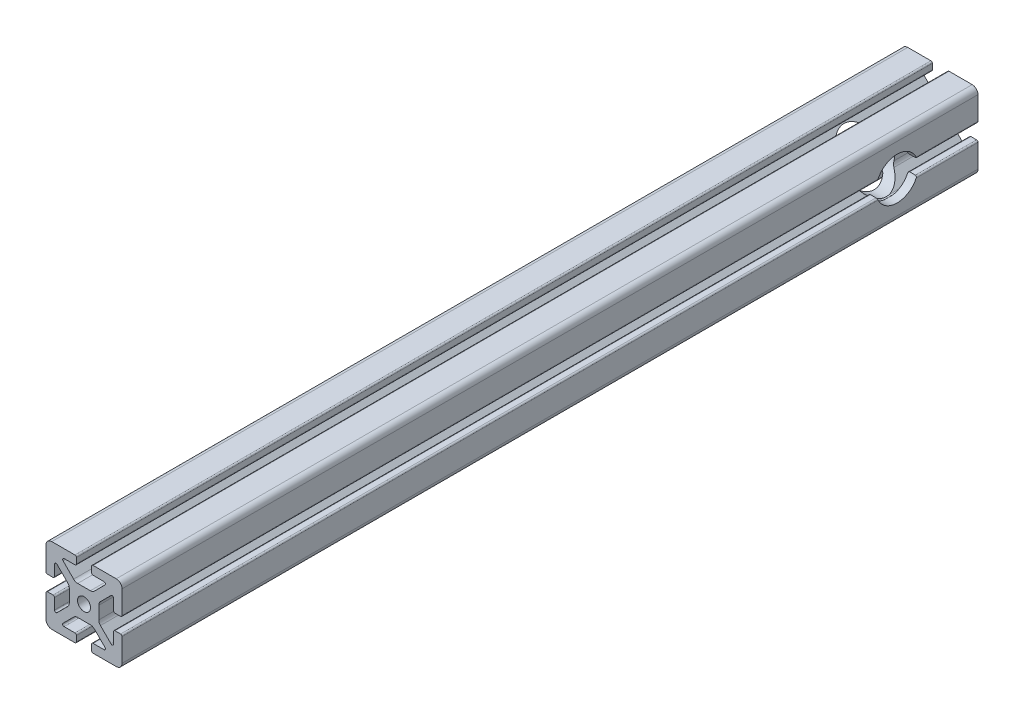
SolidWorks part; units mm, degrees
ref_plane "Front Plane" through (0, 0, 0) normal (0, 0, 1) x (1, 0, 0)
ref_plane "Top Plane" through (0, 0, 0) normal (0, 1, 0) x (1, 0, 0)
ref_plane "Right Plane" through (0, 0, 0) normal (1, 0, 0) x (0, 0, -1)
sketch "Sketch1" plane through (0, 0, 0) normal (0, 0, 1) x (1, 0, 0)
  line L0 (0, 20) -> (0, -20) construction
  line L1 (-20, 0) -> (20, 0) construction
  line L2 (-20, 16.952) -> (-20, 4.7625)
  line L3 (-16.952, 20) -> (-4.7625, 20)
  line L4 (-4.0005, 19.238) -> (-4.0005, 16.2662)
  line L5 (-4.7625, 15.5042) -> (-10.4856, 15.5042)
  line L6 (-11.0244, 14.2034) -> (-5.456, 8.6351)
  line L7 (-14.2034, 11.0244) -> (-8.6351, 5.456)
  line L8 (-15.5042, 10.4856) -> (-15.5042, 4.7625)
  line L9 (-16.2662, 4.0005) -> (-19.238, 4.0005)
  line L10 (0, 0) -> (-20, 20) construction
  line L11 (-3.3367, 7.7572) -> (3.3367, 7.7572)
  line L12 (-7.7572, 3.3367) -> (-7.7572, -3.3367)
  line L13 (16.2662, 4.0005) -> (19.238, 4.0005)
  line L14 (15.5042, 10.4856) -> (15.5042, 4.7625)
  line L15 (20, 16.952) -> (20, 4.7625)
  line L16 (16.952, 20) -> (4.7625, 20)
  line L17 (4.0005, 19.238) -> (4.0005, 16.2662)
  line L18 (4.7625, 15.5042) -> (10.4856, 15.5042)
  line L19 (7.7572, 3.3367) -> (7.7572, -3.3367)
  line L20 (11.0244, 14.2034) -> (5.456, 8.6351)
  line L21 (14.2034, 11.0244) -> (8.6351, 5.456)
  line L22 (-16.2662, -4.0005) -> (-19.238, -4.0005)
  line L23 (-15.5042, -10.4856) -> (-15.5042, -4.7625)
  line L24 (-14.2034, -11.0244) -> (-8.6351, -5.456)
  line L25 (-11.0244, -14.2034) -> (-5.456, -8.6351)
  line L26 (-4.7625, -15.5042) -> (-10.4856, -15.5042)
  line L27 (-4.0005, -19.238) -> (-4.0005, -16.2662)
  line L28 (-16.952, -20) -> (-4.7625, -20)
  line L29 (-20, -16.952) -> (-20, -4.7625)
  line L30 (20, -16.952) -> (20, -4.7625)
  line L31 (16.952, -20) -> (4.7625, -20)
  line L32 (4.0005, -19.238) -> (4.0005, -16.2662)
  line L33 (4.7625, -15.5042) -> (10.4856, -15.5042)
  line L34 (11.0244, -14.2034) -> (5.456, -8.6351)
  line L35 (14.2034, -11.0244) -> (8.6351, -5.456)
  line L36 (15.5042, -10.4856) -> (15.5042, -4.7625)
  line L37 (16.2662, -4.0005) -> (19.238, -4.0005)
  line L38 (-3.3367, -7.7572) -> (3.3367, -7.7572)
  circle A0 centre (0, 0) radius 3.4036
  arc A1 (-20, 16.952) -> (-16.952, 20) centre (-16.952, 16.952) cw
  arc A2 (-14.2034, 11.0244) -> (-15.5042, 10.4856) centre (-14.7422, 10.4856) ccw
  arc A3 (-10.4856, 15.5042) -> (-11.0244, 14.2034) centre (-10.4856, 14.7422) ccw
  arc A4 (-4.7625, 20) -> (-4.0005, 19.238) centre (-4.7625, 19.238) cw
  arc A5 (-20, 4.7625) -> (-19.238, 4.0005) centre (-19.238, 4.7625) ccw
  arc A6 (-15.5042, 4.7625) -> (-16.2662, 4.0005) centre (-16.2662, 4.7625) cw
  arc A7 (-4.0005, 16.2662) -> (-4.7625, 15.5042) centre (-4.7625, 16.2662) cw
  arc A8 (-3.3367, 7.7572) -> (-5.456, 8.6351) centre (-3.3367, 10.7544) cw
  arc A9 (-7.7572, 3.3367) -> (-8.6351, 5.456) centre (-10.7544, 3.3367) ccw
  arc A10 (15.5042, 4.7625) -> (16.2662, 4.0005) centre (16.2662, 4.7625) ccw
  arc A11 (20, 4.7625) -> (19.238, 4.0005) centre (19.238, 4.7625) cw
  arc A12 (20, 16.952) -> (16.952, 20) centre (16.952, 16.952) ccw
  arc A13 (4.7625, 20) -> (4.0005, 19.238) centre (4.7625, 19.238) ccw
  arc A14 (4.0005, 16.2662) -> (4.7625, 15.5042) centre (4.7625, 16.2662) ccw
  arc A15 (3.3367, 7.7572) -> (5.456, 8.6351) centre (3.3367, 10.7544) ccw
  arc A16 (7.7572, 3.3367) -> (8.6351, 5.456) centre (10.7544, 3.3367) cw
  arc A17 (14.2034, 11.0244) -> (15.5042, 10.4856) centre (14.7422, 10.4856) cw
  arc A18 (10.4856, 15.5042) -> (11.0244, 14.2034) centre (10.4856, 14.7422) cw
  arc A19 (-7.7572, -3.3367) -> (-8.6351, -5.456) centre (-10.7544, -3.3367) cw
  arc A20 (-3.3367, -7.7572) -> (-5.456, -8.6351) centre (-3.3367, -10.7544) ccw
  arc A21 (-4.0005, -16.2662) -> (-4.7625, -15.5042) centre (-4.7625, -16.2662) ccw
  arc A22 (-15.5042, -4.7625) -> (-16.2662, -4.0005) centre (-16.2662, -4.7625) ccw
  arc A23 (-20, -4.7625) -> (-19.238, -4.0005) centre (-19.238, -4.7625) cw
  arc A24 (-4.7625, -20) -> (-4.0005, -19.238) centre (-4.7625, -19.238) ccw
  arc A25 (-10.4856, -15.5042) -> (-11.0244, -14.2034) centre (-10.4856, -14.7422) cw
  arc A26 (-14.2034, -11.0244) -> (-15.5042, -10.4856) centre (-14.7422, -10.4856) cw
  arc A27 (-20, -16.952) -> (-16.952, -20) centre (-16.952, -16.952) ccw
  arc A28 (20, -16.952) -> (16.952, -20) centre (16.952, -16.952) cw
  arc A29 (14.2034, -11.0244) -> (15.5042, -10.4856) centre (14.7422, -10.4856) ccw
  arc A30 (10.4856, -15.5042) -> (11.0244, -14.2034) centre (10.4856, -14.7422) ccw
  arc A31 (4.7625, -20) -> (4.0005, -19.238) centre (4.7625, -19.238) cw
  arc A32 (20, -4.7625) -> (19.238, -4.0005) centre (19.238, -4.7625) ccw
  arc A33 (15.5042, -4.7625) -> (16.2662, -4.0005) centre (16.2662, -4.7625) cw
  arc A34 (4.0005, -16.2662) -> (4.7625, -15.5042) centre (4.7625, -16.2662) cw
  arc A35 (3.3367, -7.7572) -> (5.456, -8.6351) centre (3.3367, -10.7544) cw
  arc A36 (7.7572, -3.3367) -> (8.6351, -5.456) centre (10.7544, -3.3367) ccw
  point P29 (-20, 4.0005)
  point P32 (-15.5042, 4.0005)
  point P36 (-4.5782, 7.7572)
  point P68 (0, 7.7572)
  dimension "D4" = 6.8072
  dimension "D5" = 3.048
  dimension "D6" = 0.762
  dimension "D9" = 0.762
  dimension "D10" = 0.762
  dimension "D11" = 4.4958
  dimension "D13" = 2.9972
  dimension "D1" = 40
  dimension "D2" = 40
  dimension "D3" = 12.2428
  dimension "D7" = 8.001
  dimension "D8" = 4.4958
extrude "Extrude1" add sketch "Sketch1" along normal mid plane 450.22
sketch "Sketch2" plane through (20, 0, 0) normal (1, 0, 0) x (0, 0, -1)
  line L2 (225.11, -16.952) -> (225.11, -4.7625) construction
  circle A0 centre (182.565, 0) radius 11.1125
  dimension "D1" = 22.225
  dimension "D2" = 42.545
extrude "Cut-Extrude1" cut sketch "Sketch2" against normal up to surface (40 mm away) up to face at (-20, 10.8572, 0)
equation "\"D2@Sketch1\" = \"D1@Sketch1\""
